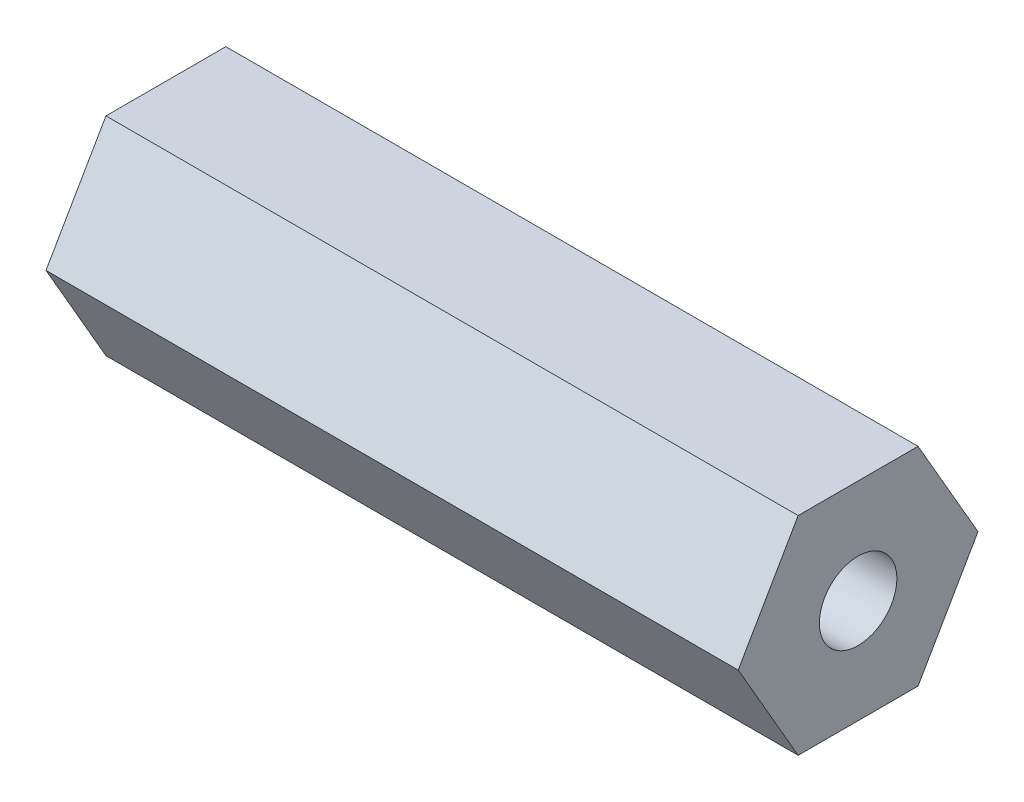
SolidWorks part; units mm, degrees
ref_plane "Front Plane" through (0, 0, 0) normal (0, 0, 1) x (1, 0, 0)
ref_plane "Top Plane" through (0, 0, 0) normal (0, 1, 0) x (1, 0, 0)
ref_plane "Right Plane" through (0, 0, 0) normal (1, 0, 0) x (0, 0, -1)
sketch "Sketch1" plane through (0, 0, 0) normal (1, 0, 0) x (0, 0, -1)
  line L0 (0, 0) -> (0, 2.3813) construction
  line L1 (-1.3748, -2.3812) -> (1.3748, -2.3812)
  line L2 (1.3748, -2.3812) -> (2.7496, 0)
  line L3 (2.7496, 0) -> (1.3748, 2.3813)
  line L4 (1.3748, 2.3813) -> (-1.3748, 2.3813)
  line L5 (-1.3748, 2.3813) -> (-2.7496, 0)
  line L6 (-2.7496, 0) -> (-1.3748, -2.3812)
  circle A0 centre (0, 0) radius 2.3812 construction
  dimension "D1" = 4.7625
extrude "Boss-Extrude1" add sketch "Sketch1" along normal blind 15.875
hole_wizard "#2-56 Tapped Hole1" positions "Sketch3" profile "Sketch2" tap size "#2-56" standard "ANSI Inch" end condition through all
sketch "Sketch3" plane through (0, 0, 0) normal (-1, 0, 0) x (0, 0, 1)
  point P0 (0, 0)
sketch "Sketch2" plane through (0, 0, 0) normal (0, 1, 0) x (0, 0, 1)
  line L0 (0, 0) -> (0, 15.875)
  line L1 (0, 15.875) -> (0.889, 15.875)
  line L2 (0.889, 15.875) -> (0.889, 0)
  line L5 (0.889, 0) -> (0, 0)
  line L11 (0, -6.35) -> (0, 107.95) construction
  dimension "Thru Tap Drill Dia." = 1.778
  dimension "Thru Tap Drill Depth" = 15.875
cosmetic thread "Hole Thread1" parameters "D2"=2.1844
